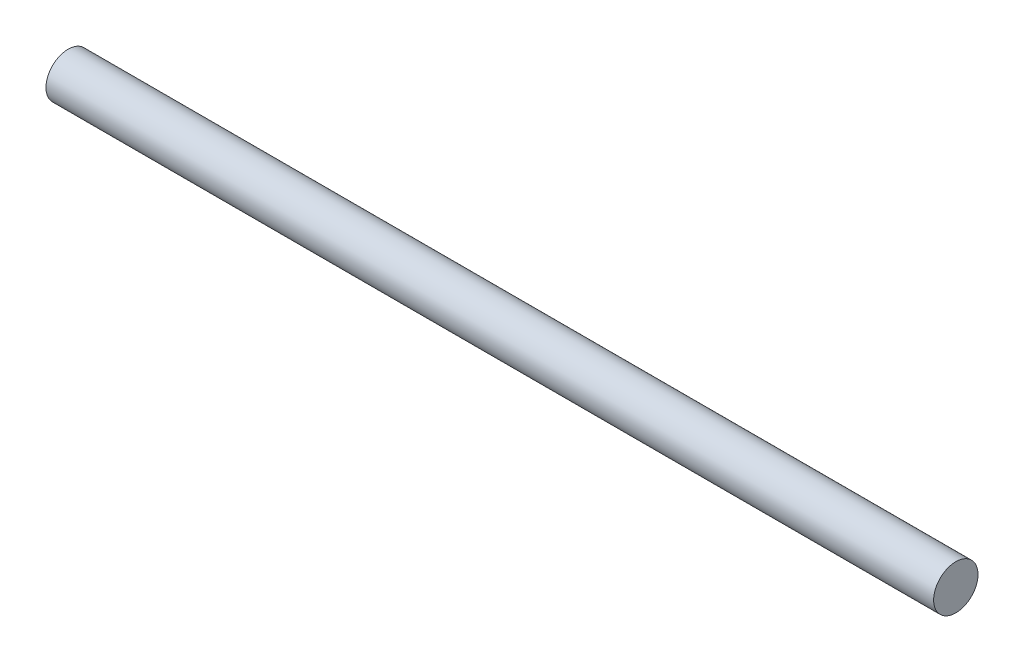
SolidWorks part; units mm, degrees
ref_plane "Front Plane" through (0, 0, 0) normal (0, 0, 1) x (1, 0, 0)
ref_plane "Top Plane" through (0, 0, 0) normal (0, 1, 0) x (1, 0, 0)
ref_plane "Right Plane" through (0, 0, 0) normal (1, 0, 0) x (0, 0, -1)
sketch "Sketch1" plane through (0, 0, 0) normal (1, 0, 0) x (0, 0, -1)
  circle A0 centre (0, 0) radius 0.05
  dimension "D1" = 0.1
extrude "Boss-Extrude2" add sketch "Sketch1" along normal blind 2
